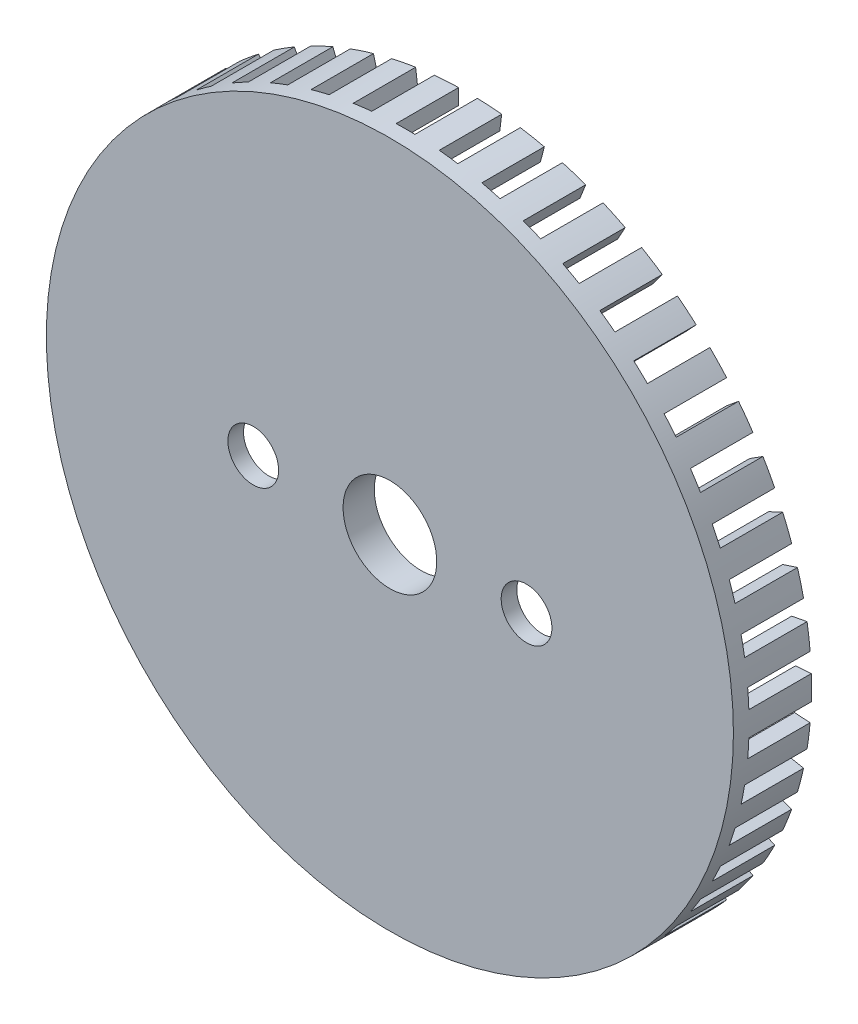
SolidWorks part; units mm, degrees
ref_plane "Plano frontal" through (0, 0, 0) normal (0, 0, 1) x (1, 0, 0)
ref_plane "Plano superior" through (0, 0, 0) normal (0, 1, 0) x (1, 0, 0)
ref_plane "Plano direito" through (0, 0, 0) normal (1, 0, 0) x (0, 0, -1)
sketch "Esboço1" plane through (0, 0, 0) normal (0, 0, 1) x (1, 0, 0)
  circle A0 centre (0, 0) radius 22
  dimension "D1" = 44
extrude "Ressalto-extrusão1" add sketch "Esboço1" along normal blind 5
shell "Casca1" thickness 1
sketch "Esboço3" plane through (0, 0, 0) normal (0, 1, 0) x (1, 0, 0)
  line L1 (-0.6, 0) -> (0.6, 0)
  line L2 (-0.6, 0) -> (-0.6, -4)
  line L3 (-0.6, -4) -> (0.6, -4)
  line L4 (0.6, 0) -> (0.6, -4)
  point P6 (0, 0)
  dimension "D1" = 0.6
  dimension "D2" = 0.6
  dimension "D3" = 4
extrude "Corte-extrusão1" cut sketch "Esboço3" along normal through all from offset 10
pattern_circular "PadrãoCircular1" count 50 over 360 about axis through (0, 0, 0) along (0, 0, 1) of "Corte-extrusão1"
sketch "Esboço12" plane through (0, 0, 5) normal (0, 0, 1) x (1, 0, 0)
  line L0 (0, 0) -> (0, 22) construction
  circle A0 centre (-8.75, 0) radius 1.625
  circle A1 centre (0, 0) radius 22 construction
  circle A2 centre (8.75, 0) radius 1.625
  dimension "D1" = 8.75
  dimension "D2" = 3.25
extrude "Corte-extrusão4" cut sketch "Esboço12" against normal through all
sketch "Esboço15" plane through (0, 0, 4) normal (0, 0, -1) x (-1, 0, 0)
  circle A0 centre (0, 0) radius 4.4
  dimension "D1" = 8.8
extrude "Ressalto-extrusão6" add sketch "Esboço15" along normal blind 1
sketch "Esboço16" plane through (0, 0, 3) normal (0, 0, -1) x (-1, 0, 0)
  circle A0 centre (0, 0) radius 3
  dimension "D1" = 6
extrude "Corte-extrusão5" cut sketch "Esboço16" against normal through all
